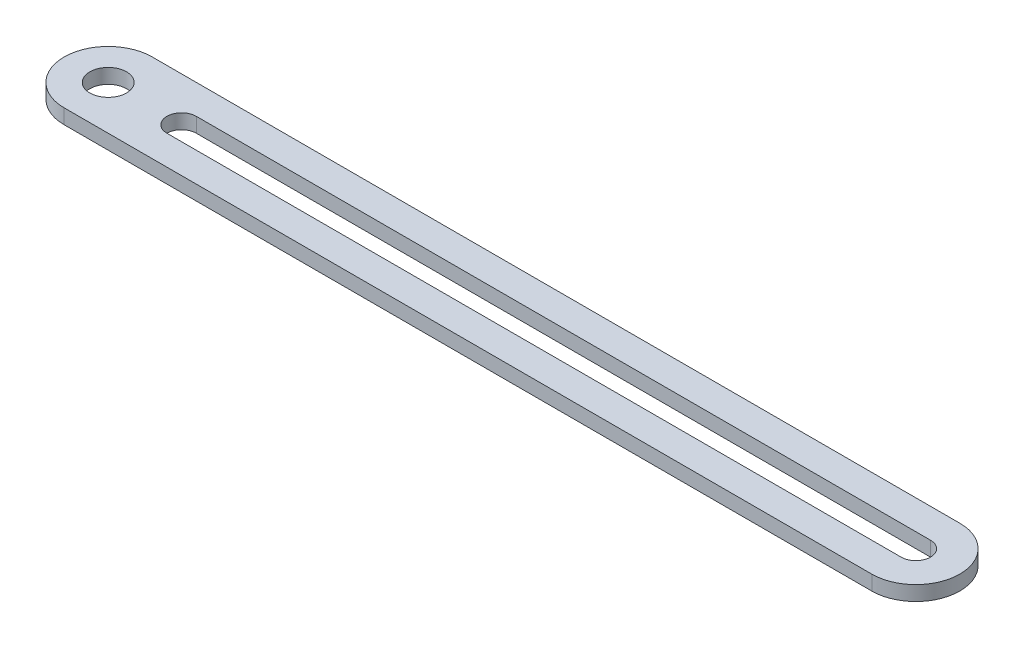
SolidWorks part; units mm, degrees
ref_plane "Front Plane" through (0, 0, 0) normal (0, 0, 1) x (1, 0, 0)
ref_plane "Top Plane" through (0, 0, 0) normal (0, 1, 0) x (1, 0, 0)
ref_plane "Right Plane" through (0, 0, 0) normal (1, 0, 0) x (0, 0, -1)
sketch "Sketch1" plane through (0, 0, 0) normal (0, 1, 0) x (1, 0, 0)
  line L0 (10, 0) -> (110, 0) construction
  line L1 (10, 2) -> (110, 2)
  line L2 (10, -2) -> (110, -2)
  line L3 (0, 0) -> (110, 0) construction
  line L4 (0, 6) -> (110, 6)
  line L5 (0, -6) -> (110, -6)
  circle A0 centre (0, 0) radius 2.5
  arc A1 (10, 2) -> (10, -2) centre (10, 0) ccw
  arc A2 (110, -2) -> (110, 2) centre (110, 0) ccw
  arc A3 (0, 6) -> (0, -6) centre (0, 0) ccw
  arc A4 (110, -6) -> (110, 6) centre (110, 0) ccw
  point P5 (60, 0)
  point P10 (55, 0)
  dimension "D1" = 5
  dimension "D5" = 6
  dimension "D2" = 10
  dimension "D3" = 100
  dimension "D4" = 4
extrude "Boss-Extrude1" add sketch "Sketch1" along normal blind 2
